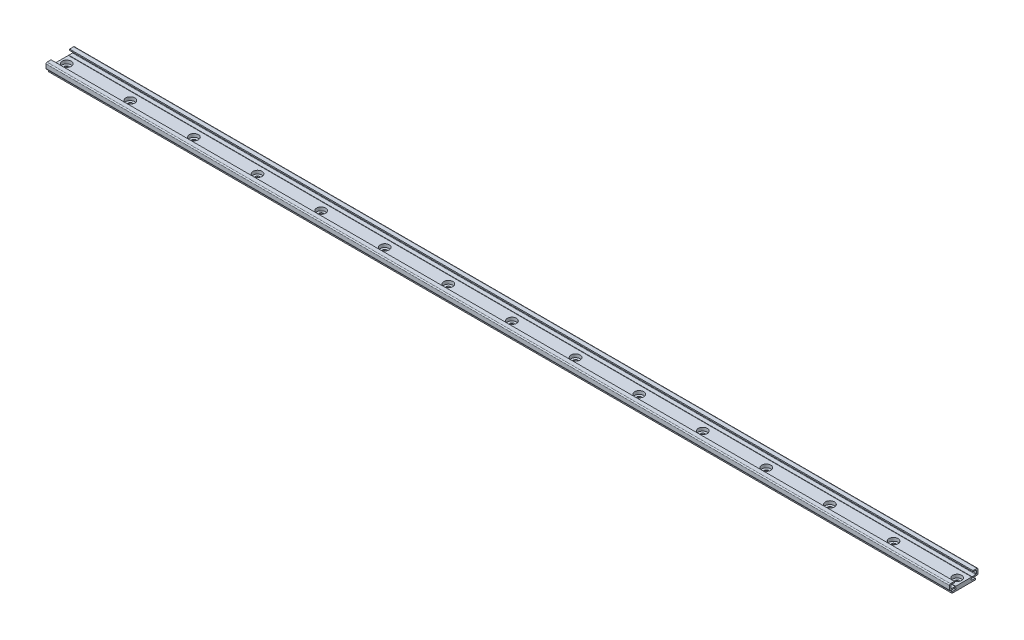
SolidWorks part; units mm, degrees
ref_plane "Front" through (0, 0, 0) normal (0, 0, 1) x (1, 0, 0)
ref_plane "Top" through (0, 0, 0) normal (0, 1, 0) x (1, 0, 0)
ref_plane "Right" through (0, 0, 0) normal (1, 0, 0) x (0, 0, -1)
sketch "Sketch1" plane through (0, 0, 0) normal (1, 0, 0) x (0, 0, -1)
  line L0 (0, -4.35) -> (0, 4.35) construction
  line L10 (-11, -4.35) -> (11, -4.35)
  line L11 (11, -4.35) -> (11, -3.05)
  line L12 (10.8, -2.85) -> (7.8, -2.85)
  line L13 (7.8, -1.35) -> (12.5, -1.35)
  line L14 (13.5, -0.35) -> (13.5, 3.35)
  line L15 (12.5, 4.35) -> (8.75, 4.35)
  line L16 (8.75, 4.35) -> (8.75, 3.25)
  line L17 (8.75, 3.25) -> (11.5, 3.25)
  line L18 (12, 2.75) -> (12, 0.25)
  line L19 (11.5, -0.25) -> (7.95, -0.25)
  line L20 (7.55, -0.25) -> (-7.55, -0.25)
  line L21 (-11.5, -0.25) -> (-7.95, -0.25)
  line L22 (-12, 2.75) -> (-12, 0.25)
  line L23 (-8.75, 3.25) -> (-11.5, 3.25)
  line L24 (-8.75, 4.35) -> (-8.75, 3.25)
  line L25 (-12.5, 4.35) -> (-8.75, 4.35)
  line L26 (-13.5, -0.35) -> (-13.5, 3.35)
  line L27 (-7.8, -1.35) -> (-12.5, -1.35)
  line L28 (-10.8, -2.85) -> (-7.8, -2.85)
  line L29 (-11, -4.35) -> (-11, -3.05)
  line L39 (-13.5, -4.35) -> (13.5, -4.35) construction
  arc A2 (11, -3.05) -> (10.8, -2.85) centre (10.8, -3.05) ccw
  arc A3 (7.8, -1.35) -> (7.8, -2.85) centre (7.8, -2.1) ccw
  arc A4 (12.5, -1.35) -> (13.5, -0.35) centre (12.5, -0.35) ccw
  arc A5 (13.5, 3.35) -> (12.5, 4.35) centre (12.5, 3.35) ccw
  arc A6 (12, 2.75) -> (11.5, 3.25) centre (11.5, 2.75) ccw
  arc A7 (11.5, -0.25) -> (12, 0.25) centre (11.5, 0.25) ccw
  arc A8 (7.55, -0.25) -> (7.95, -0.25) centre (7.75, -0.25) ccw
  arc A9 (-7.55, -0.25) -> (-7.95, -0.25) centre (-7.75, -0.25) cw
  arc A10 (-11.5, -0.25) -> (-12, 0.25) centre (-11.5, 0.25) cw
  arc A11 (-12, 2.75) -> (-11.5, 3.25) centre (-11.5, 2.75) cw
  arc A12 (-13.5, 3.35) -> (-12.5, 4.35) centre (-12.5, 3.35) cw
  arc A13 (-12.5, -1.35) -> (-13.5, -0.35) centre (-12.5, -0.35) cw
  arc A14 (-7.8, -1.35) -> (-7.8, -2.85) centre (-7.8, -2.1) cw
  arc A15 (-11, -3.05) -> (-10.8, -2.85) centre (-10.8, -3.05) cw
  point P26 (0, 0)
  point P32 (0, -3.35)
  point P37 (0, -0.25)
  dimension "D1" = 0.2
  dimension "D2" = 0.75
  dimension "D3" = 1
  dimension "D4" = 0.5
  dimension "Rail Height" = 8.7
  dimension "D5" = 7.75
  dimension "D6" = 7.8
  dimension "D7" = 8.75
  dimension "D8" = 11
  dimension "D9" = 3.25
  dimension "D10" = 0.25
  dimension "D11" = 1.35
  dimension "Rail Width" = 27
  dimension "Mounting Hole Depth" = 1
sketch "Sketch2" plane through (0, 0, 0) normal (0, 0, 1) x (1, 0, 0)
  line L0 (500, 0) -> (-500, 0) construction
  line L1 (-478, 0) -> (-482, 0)
  point P0 (-480, 0)
  point P3 (-420, 0)
  point P4 (0, 0)
  point P6 (-412, 0)
  point P7 (494, 0)
  dimension "Rail Length" = 1000
  dimension "Mounting Hole Ctr to End" = 20
  dimension "Mounting Hole Ctr to Ctr" = 60
  dimension "D2" = 6
  dimension "D1" = 8
  dimension "For Mounting Fastener Thread Size" = 4
sketch "Sketch5" plane through (0, 0, 0) normal (1, 0, 0) x (0, 0, -1)
  line L38 (8.75, 4.35) -> (8.75, 3.25) construction
  line L39 (12.5, 4.35) -> (8.75, 4.35) construction
  line L40 (13.5, -0.35) -> (13.5, 3.35) construction
  line L41 (7.8, -1.35) -> (12.5, -1.35) construction
  line L42 (10.8, -2.85) -> (7.8, -2.85) construction
  line L43 (11, -4.35) -> (11, -3.05) construction
  line L44 (-11, -4.35) -> (11, -4.35) construction
  line L45 (-11, -4.35) -> (-11, -3.05) construction
  line L46 (-10.8, -2.85) -> (-7.8, -2.85) construction
  line L47 (-7.8, -1.35) -> (-12.5, -1.35) construction
  line L48 (-13.5, -0.35) -> (-13.5, 3.35) construction
  line L49 (-12.5, 4.35) -> (-8.75, 4.35) construction
  line L50 (-8.75, 4.35) -> (-8.75, 3.25) construction
  line L51 (-8.75, 3.25) -> (-11.5, 3.25) construction
  line L52 (-12, 2.75) -> (-12, 0.25) construction
  line L53 (-11.5, -0.25) -> (-7.95, -0.25) construction
  line L54 (7.55, -0.25) -> (-7.55, -0.25) construction
  line L55 (11.5, -0.25) -> (7.95, -0.25) construction
  line L56 (12, 2.75) -> (12, 0.25) construction
  line L57 (8.75, 3.25) -> (11.5, 3.25) construction
  line L58 (8.75, 4.35) -> (8.75, 3.25)
  line L59 (12.5, 4.35) -> (8.75, 4.35)
  line L60 (13.5, -0.35) -> (13.5, 3.35)
  line L61 (7.8, -1.35) -> (12.5, -1.35)
  line L62 (10.8, -2.85) -> (7.8, -2.85)
  line L63 (11, -4.35) -> (11, -3.05)
  line L64 (-11, -4.35) -> (11, -4.35)
  line L65 (-11, -4.35) -> (-11, -3.05)
  line L66 (-10.8, -2.85) -> (-7.8, -2.85)
  line L67 (-7.8, -1.35) -> (-12.5, -1.35)
  line L68 (-13.5, -0.35) -> (-13.5, 3.35)
  line L69 (-12.5, 4.35) -> (-8.75, 4.35)
  line L70 (-8.75, 4.35) -> (-8.75, 3.25)
  line L71 (-8.75, 3.25) -> (-11.5, 3.25)
  line L72 (-12, 2.75) -> (-12, 0.25)
  line L73 (-11.5, -0.25) -> (-7.95, -0.25)
  line L74 (7.55, -0.25) -> (-7.55, -0.25)
  line L75 (11.5, -0.25) -> (7.95, -0.25)
  line L76 (12, 2.75) -> (12, 0.25)
  line L77 (8.75, 3.25) -> (11.5, 3.25)
  arc A4 (13.5, 3.35) -> (12.5, 4.35) centre (12.5, 3.35) ccw construction
  arc A5 (12.5, -1.35) -> (13.5, -0.35) centre (12.5, -0.35) ccw construction
  arc A6 (7.8, -1.35) -> (7.8, -2.85) centre (7.8, -2.1) ccw construction
  arc A7 (11, -3.05) -> (10.8, -2.85) centre (10.8, -3.05) ccw construction
  arc A8 (-10.8, -2.85) -> (-11, -3.05) centre (-10.8, -3.05) ccw construction
  arc A9 (-7.8, -2.85) -> (-7.8, -1.35) centre (-7.8, -2.1) ccw construction
  arc A10 (-13.5, -0.35) -> (-12.5, -1.35) centre (-12.5, -0.35) ccw construction
  arc A11 (-12.5, 4.35) -> (-13.5, 3.35) centre (-12.5, 3.35) ccw construction
  arc A12 (-11.5, 3.25) -> (-12, 2.75) centre (-11.5, 2.75) ccw construction
  arc A13 (-12, 0.25) -> (-11.5, -0.25) centre (-11.5, 0.25) ccw construction
  arc A14 (-7.95, -0.25) -> (-7.55, -0.25) centre (-7.75, -0.25) ccw construction
  arc A15 (7.55, -0.25) -> (7.95, -0.25) centre (7.75, -0.25) ccw construction
  arc A16 (11.5, -0.25) -> (12, 0.25) centre (11.5, 0.25) ccw construction
  arc A17 (12, 2.75) -> (11.5, 3.25) centre (11.5, 2.75) ccw construction
  arc A18 (13.5, 3.35) -> (12.5, 4.35) centre (12.5, 3.35) ccw
  arc A19 (12.5, -1.35) -> (13.5, -0.35) centre (12.5, -0.35) ccw
  arc A20 (7.8, -1.35) -> (7.8, -2.85) centre (7.8, -2.1) ccw
  arc A21 (11, -3.05) -> (10.8, -2.85) centre (10.8, -3.05) ccw
  arc A22 (-10.8, -2.85) -> (-11, -3.05) centre (-10.8, -3.05) ccw
  arc A23 (-7.8, -2.85) -> (-7.8, -1.35) centre (-7.8, -2.1) ccw
  arc A24 (-13.5, -0.35) -> (-12.5, -1.35) centre (-12.5, -0.35) ccw
  arc A25 (-12.5, 4.35) -> (-13.5, 3.35) centre (-12.5, 3.35) ccw
  arc A26 (-11.5, 3.25) -> (-12, 2.75) centre (-11.5, 2.75) ccw
  arc A27 (-12, 0.25) -> (-11.5, -0.25) centre (-11.5, 0.25) ccw
  arc A28 (-7.95, -0.25) -> (-7.55, -0.25) centre (-7.75, -0.25) ccw
  arc A29 (7.55, -0.25) -> (7.95, -0.25) centre (7.75, -0.25) ccw
  arc A30 (11.5, -0.25) -> (12, 0.25) centre (11.5, 0.25) ccw
  arc A31 (12, 2.75) -> (11.5, 3.25) centre (11.5, 2.75) ccw
extrude "Boss-Extrude1" add sketch "Sketch5" along normal up to vertex (500 mm away) and the other way up to vertex (500 mm away)
sketch "Sketch3" plane through (0, 0, 0) normal (0, 0, 1) x (1, 0, 0)
  line L0 (-484.25, 0) -> (-484.25, -3.35)
  line L1 (-484.25, -3.35) -> (-482, -3.35)
  line L2 (-482, -3.35) -> (-482, -4.35)
  line L3 (-482, -4.35) -> (-480, -4.35)
  line L4 (-480, -4.35) -> (-480, 0)
  line L5 (-480, 0) -> (-484.25, 0)
  line L6 (500, -4.35) -> (-500, -4.35) construction
  line L8 (-484.25, 0) -> (-475.75, 0) construction
  line L10 (-478, -4.35) -> (-482, -4.35) construction
  dimension "D2" = 8.5
revolve "Cut-Revolve1" cut sketch "Sketch3" angle 360 mid plane about L4
pattern_linear "LPattern1" count 17 spacing 60 along (1, 0, 0) of "Cut-Revolve1"
sketch "Sketch6" plane through (0, 4.35, 0) normal (0, 1, 0) x (1, 0, 0)
  line L1 (-500, 13.5) -> (376.3, 13.5)
  line L2 (-500, 13.5) -> (-500, -272.6408)
  line L3 (-500, -272.6408) -> (376.3, -272.6408)
  line L4 (376.3, 13.5) -> (376.3, -272.6408)
  line L6 (376.3, -272.6408) -> (559.2455, -272.6408)
  line L7 (376.3, -272.6408) -> (376.3, 112.7464)
  line L8 (376.3, 112.7464) -> (559.2455, 112.7464)
  line L9 (559.2455, -272.6408) -> (559.2455, 112.7464)
  line M2 (500, 12.5) -> (-500, 12.5)
  line M4 (-500, 8.75) -> (500, 8.75)
  line M5 (500, 8.75) -> (500, 12.5)
  dimension "D1" = 876.3
extrude "Cut-Extrude1" cut sketch "Sketch6" against normal through all contours L6 L9 L8 L7 L4 M2 M5 M4 | L4 M2 M4 M5
sketch "Sketch7" plane through (0, 4.35, 0) normal (0, 1, 0) x (1, 0, 0)
  line L1 (366.14, 13.5) -> (376.3, 13.5)
  line L2 (366.14, 13.5) -> (366.14, -43.915)
  line L3 (366.14, -43.915) -> (376.3, -43.915)
  line L4 (376.3, 13.5) -> (376.3, -43.915)
  point P7 (0, 0)
  dimension "D1" = 10.16
extrude "Cut-Extrude2" cut sketch "Sketch7" against normal through all
sketch "Sketch8" plane through (0, 4.35, 0) normal (0, 1, 0) x (1, 0, 0)
  line L1 (-500, 13.5) -> (-486.03, 13.5)
  line L2 (-500, 13.5) -> (-500, -35.8617)
  line L3 (-500, -35.8617) -> (-486.03, -35.8617)
  line L4 (-486.03, 13.5) -> (-486.03, -35.8617)
  dimension "D1" = 13.97
extrude "Cut-Extrude3" cut sketch "Sketch8" against normal through all
equation "\"D3@LPattern1\"=\"Mounting Hole Ctr to Ctr@Sketch2\""
equation "\"D2@Sketch2\"=\"Mounting Hole Ctr to End@Sketch2\"*.3"
equation "\"D1@Sketch2\"=\"Mounting Hole Ctr to End@Sketch2\"*.4"
